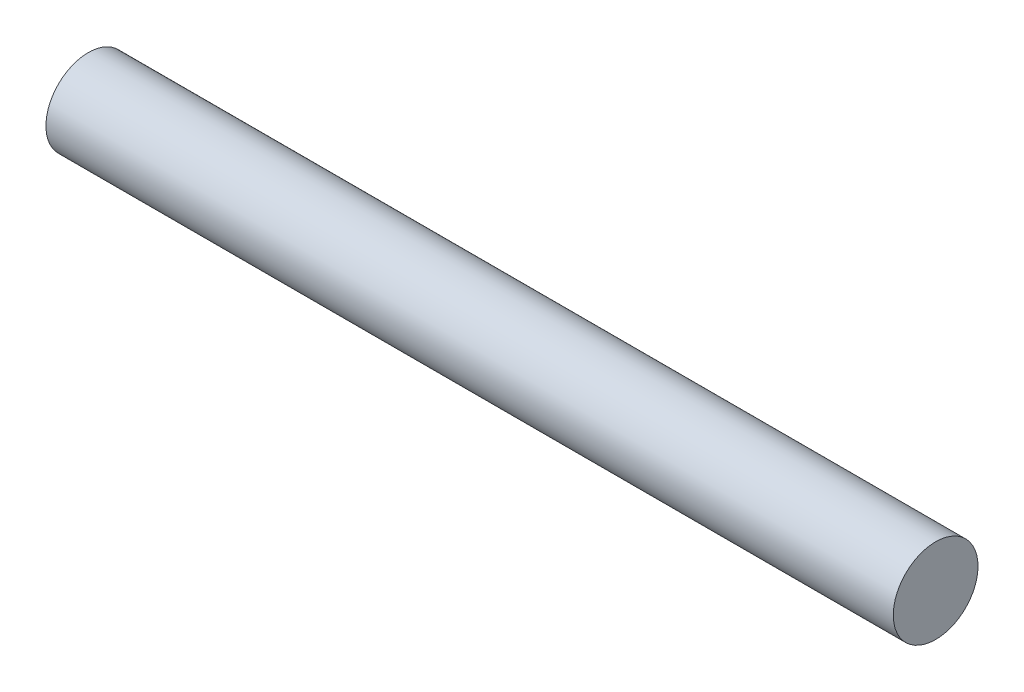
SolidWorks part; units mm, degrees
material "Chrome Stainless Steel"
ref_plane "Front Plane" through (0, 0, 0) normal (0, 0, 1) x (1, 0, 0)
ref_plane "Top Plane" through (0, 0, 0) normal (0, 1, 0) x (1, 0, 0)
ref_plane "Right Plane" through (0, 0, 0) normal (1, 0, 0) x (0, 0, -1)
sketch "Sketch1" plane through (0, 0, 0) normal (1, 0, 0) x (0, 0, -1)
  circle A0 centre (0, 0) radius 1.5875
  dimension "D1" = 3.175
extrude "Boss-Extrude1" add sketch "Sketch1" along normal blind 31.75
